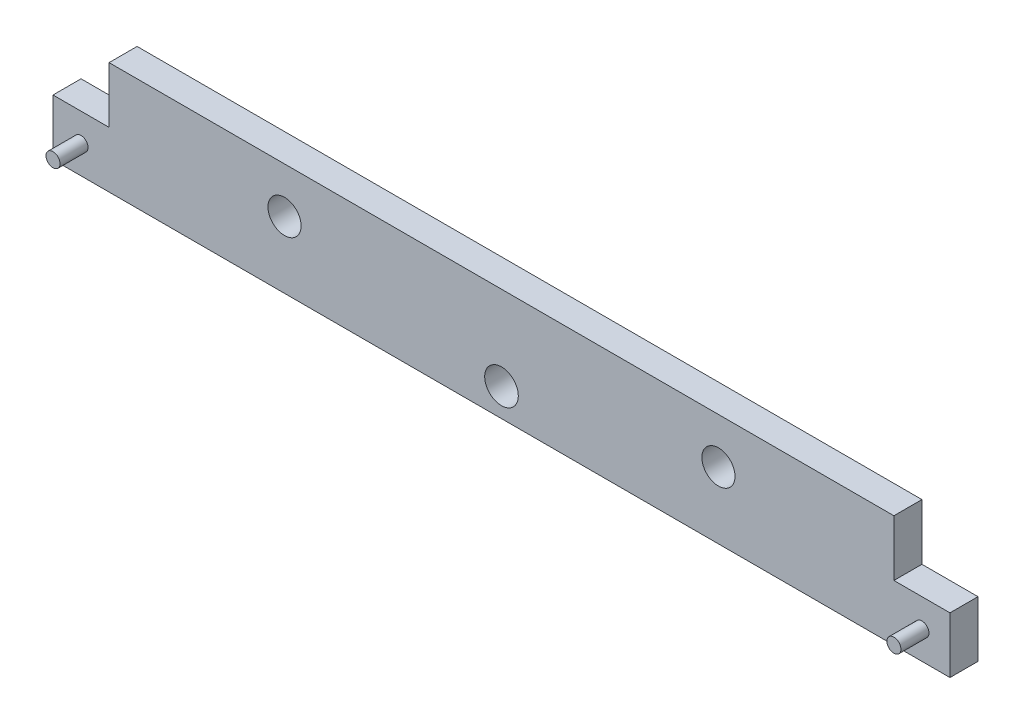
SolidWorks part; units mm, degrees
ref_plane "Front Plane" through (0, 0, 0) normal (0, 0, 1) x (1, 0, 0)
ref_plane "Top Plane" through (0, 0, 0) normal (0, 1, 0) x (1, 0, 0)
ref_plane "Right Plane" through (0, 0, 0) normal (1, 0, 0) x (0, 0, -1)
sketch "Sketch1" plane through (0, 0, 0) normal (0, 0, 1) x (1, 0, 0)
  line L1 (0, 0) -> (-320, 0)
  line L2 (0, 0) -> (0, 20)
  line L3 (0, 20) -> (-320, 20)
  line L4 (-320, 0) -> (-320, 20)
  dimension "D1" = 20
  dimension "D2" = 320
extrude "Boss-Extrude1" add sketch "Sketch1" along normal blind 10
sketch "Sketch2" plane through (0, 0, 10) normal (0, 0, 1) x (1, 0, 0)
  line L0 (0, 10) -> (-31.3515, 10) construction
  line L1 (0, 0) -> (0, 20) construction
  line L2 (-10, -14.8173) -> (-10, 31.8108) construction
  circle A0 centre (-10, 10) radius 2.5
  dimension "D2" = 5
  dimension "D1" = 10
extrude "Boss-Extrude2" add sketch "Sketch2" along normal blind 10
ref_plane "Plane1" through (-160, 0, 0) normal (1, 0, 0) x (0, 0, -1)
mirror "Mirror1" about plane through (-160, 0, 0) normal (1, 0, 0) of "Boss-Extrude2"
sketch "Sketch4" plane through (0, 0, 10) normal (0, 0, 1) x (1, 0, 0)
  line L0 (-160, -5.5) -> (-160, 5.5) construction
  line L1 (-320, 0) -> (0, 0) construction
  line L2 (0, 20) -> (-320, 20) construction
  circle A0 centre (-160, 10) radius 6
  dimension "D2" = 12
  dimension "D3" = 10
  dimension "D5" = 12
  dimension "D6" = 12
  dimension "D1" = 0
  dimension "D4" = 10
extrude "Cut-Extrude1" cut sketch "Sketch4" against normal blind 60
sketch "Sketch5" plane through (0, 20, 0) normal (0, 1, 0) x (1, 0, 0)
  line L0 (0, -10) -> (-320, -10) construction
  line L1 (-20, -10) -> (-300, -10)
  line L2 (-20, -10) -> (-20, 0)
  line L3 (-20, 0) -> (-300, 0)
  line L4 (-300, -10) -> (-300, 0)
  line L5 (0, 0) -> (-320, 0) construction
  line L6 (-320, -10) -> (-320, 0) construction
  line L7 (0, -10) -> (0, 0) construction
  dimension "D1" = 20
  dimension "D2" = 20
extrude "Boss-Extrude3" add sketch "Sketch5" along normal blind 20
sketch "Sketch6" plane through (0, 0, 0) normal (0, 0, -1) x (-1, 0, 0)
  circle A0 centre (237.4014, 23.7773) radius 5.9129
extrude "Cut-Extrude2" cut sketch "Sketch6" against normal blind 20
mirror "Mirror2" about plane through (-160, 0, 0) normal (1, 0, 0) of "Cut-Extrude2"
